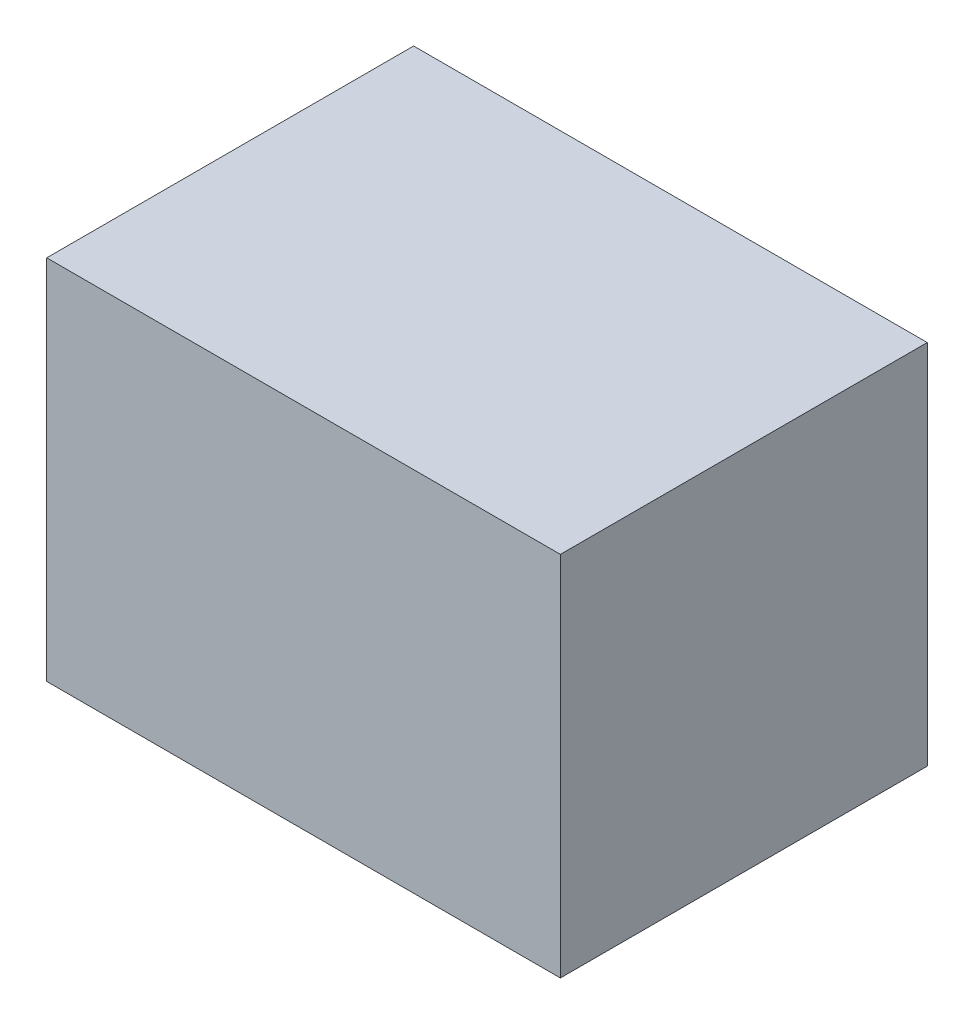
SolidWorks part; units mm, degrees
material "Custom Plastic"
ref_plane "X-Y Datum" through (0, 0, 0) normal (0, 0, 1) x (1, 0, 0)
ref_plane "X-Z Datum" through (0, 0, 0) normal (0, 1, 0) x (1, 0, 0)
ref_plane "Y-Z Datum" through (0, 0, 0) normal (1, 0, 0) x (0, 0, -1)
sketch "Sketch1" plane through (0, 0, 0) normal (1, 0, 0) x (0, 0, -1)
  line L1 (0, 0) -> (38.1, 0)
  line L2 (0, 0) -> (0, 38.1)
  line L3 (0, 38.1) -> (38.1, 38.1)
  line L4 (38.1, 0) -> (38.1, 38.1)
  dimension "D1" = 38.1
  dimension "D2" = 38.1
extrude "Boss-Extrude1" add sketch "Sketch1" along normal blind 53.34
